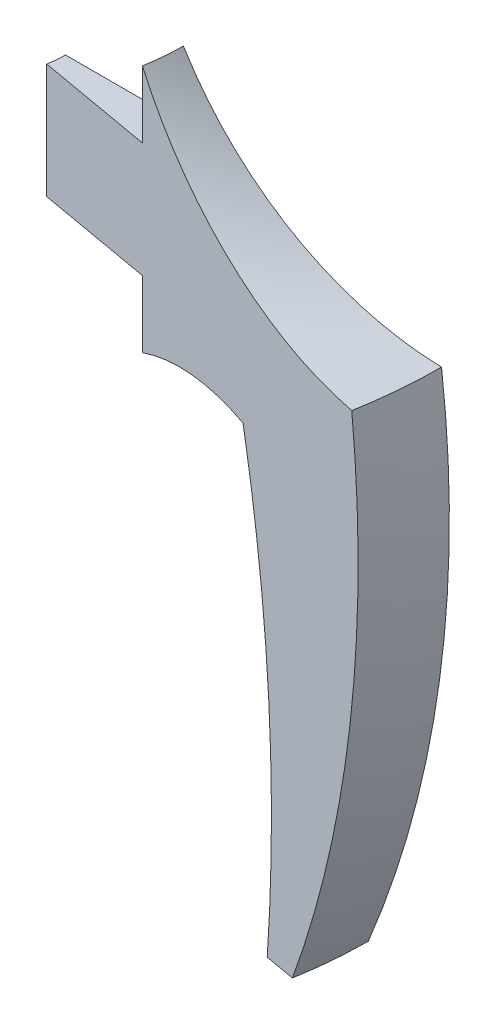
SolidWorks part; units mm, degrees
ref_plane "Front Plane" through (0, 0, 0) normal (0, 0, 1) x (1, 0, 0)
ref_plane "Top Plane" through (0, 0, 0) normal (0, 1, 0) x (1, 0, 0)
ref_plane "Right Plane" through (0, 0, 0) normal (1, 0, 0) x (0, 0, -1)
sketch "Sketch2" plane through (0, 0, 0) normal (0, 0, 1) x (1, 0, 0)
  line L0 (0, 0) -> (35, 0) construction
  line L1 (35, -20) -> (55, -18.2502) construction
  line L2 (76.5841, -4.0086) -> (64.7952, -90) construction
  line L3 (59.7952, -90) -> (64.7952, -90)
  line L4 (35, -20) -> (35, 20)
  line L5 (35, 20) -> (35, 0) construction
  line L6 (16, -9.25) -> (16, 9.25)
  line L7 (16, 9.25) -> (35, 9.25)
  line L8 (35, -9.25) -> (16, -9.25)
  line L9 (35, 20) -> (76.5841, -4.0086) construction
  line L10 (55, -18.2502) -> (59.7952, -90)
  line L11 (0, 0) -> (0, -20)
  line L14 (0, 0) -> (16, 0)
  arc A0 (35, 20) -> (76.5841, -4.0086) centre (77.7214, 45.9785) ccw
  arc A1 (76.5841, -4.0086) -> (64.7952, -90) centre (-92.1545, -24.6794) cw
  arc A2 (55, -18.2502) -> (59.7952, -90) centre (-179.3657, -69.9487) cw
  arc A3 (55, -18.2502) -> (35, -20) centre (47.464, -47.2883) ccw
  point P13 (35, 20)
  point P14 (35, 20)
  point P16 (35, 0)
  point P19 (16, 0)
  point P26 (44.8493, -17.4024)
  dimension "D5" = 240
  dimension "D6" = 85
  dimension "D7" = 90
  dimension "D8" = 170
  dimension "D10" = 20
  dimension "D11" = 30
  dimension "D14" = 50
  dimension "D2" = 18.5
  dimension "D3" = 40
  dimension "D4" = 19
  dimension "D9" = 5
  dimension "D12" = 85.9914
  dimension "D13" = 60
  dimension "D15" = 112.194
  dimension "D16" = 16
  dimension "D17" = 20
revolve "Revolve1" add sketch "Sketch2" angle 10 about L11
